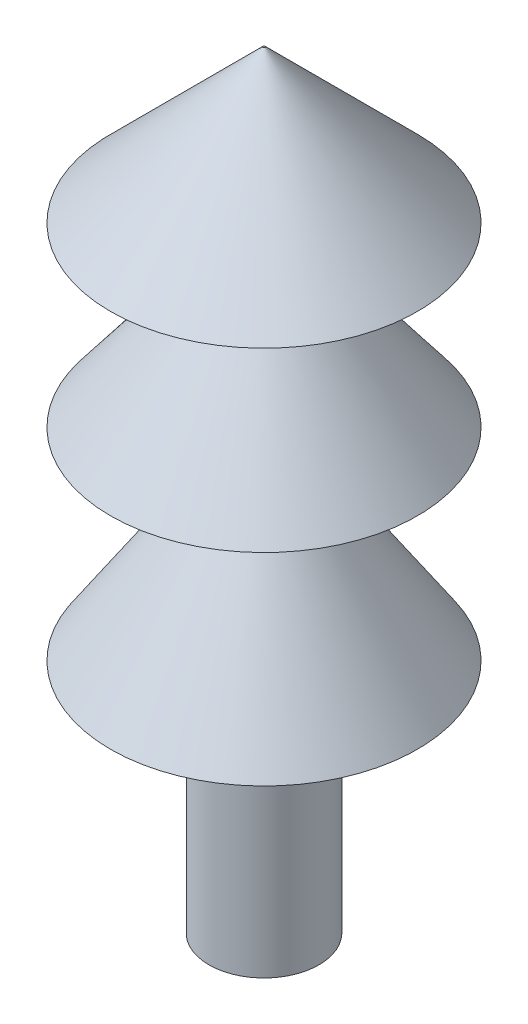
SolidWorks part; units mm, degrees
material "山毛榉"
ref_plane "前视基准面" through (0, 0, 0) normal (0, 0, 1) x (1, 0, 0)
ref_plane "上视基准面" through (0, 0, 0) normal (0, 1, 0) x (1, 0, 0)
ref_plane "右视基准面" through (0, 0, 0) normal (1, 0, 0) x (0, 0, -1)
sketch "草图1" plane through (0, 0, 0) normal (0, 1, 0) x (1, 0, 0)
  circle A0 centre (0, 0) radius 8
extrude "凸台-拉伸1" add sketch "草图1" along normal blind 40
sketch "草图2" plane through (0, 0, 0) normal (1, 0, 0) x (0, 0, -1)
  line L0 (0, 40) -> (0, 0) construction
  line L1 (8, 40) -> (-8, 40) construction
  line L2 (-0.0554, 40) -> (-8, 32.0554)
  line L3 (-8, 32.0554) -> (-0.9359, 32.0554)
  line L4 (-0.9359, 32.0554) -> (-8, 22.8329)
  line L5 (-8, 22.8329) -> (-0.9359, 22.8329)
  line L6 (-0.9359, 22.8329) -> (-8, 12.2957)
  line L8 (-8, 40) -> (-8, 0) construction
  line L9 (-8, 12.2957) -> (-2.8677, 12.2957)
  line L10 (-2.8677, 12.2957) -> (-2.8677, -1.227)
  line L11 (-2.8677, -1.227) -> (-16.7416, 0.7049)
  line L12 (-16.7416, 0.7049) -> (-12.9658, 40)
  line L13 (-12.9658, 40) -> (-8.8388, 42.3266)
  line L14 (-8.8388, 42.3266) -> (-0.0554, 40)
revolve "切除-旋转1" cut sketch "草图2" angle 360 about L0
